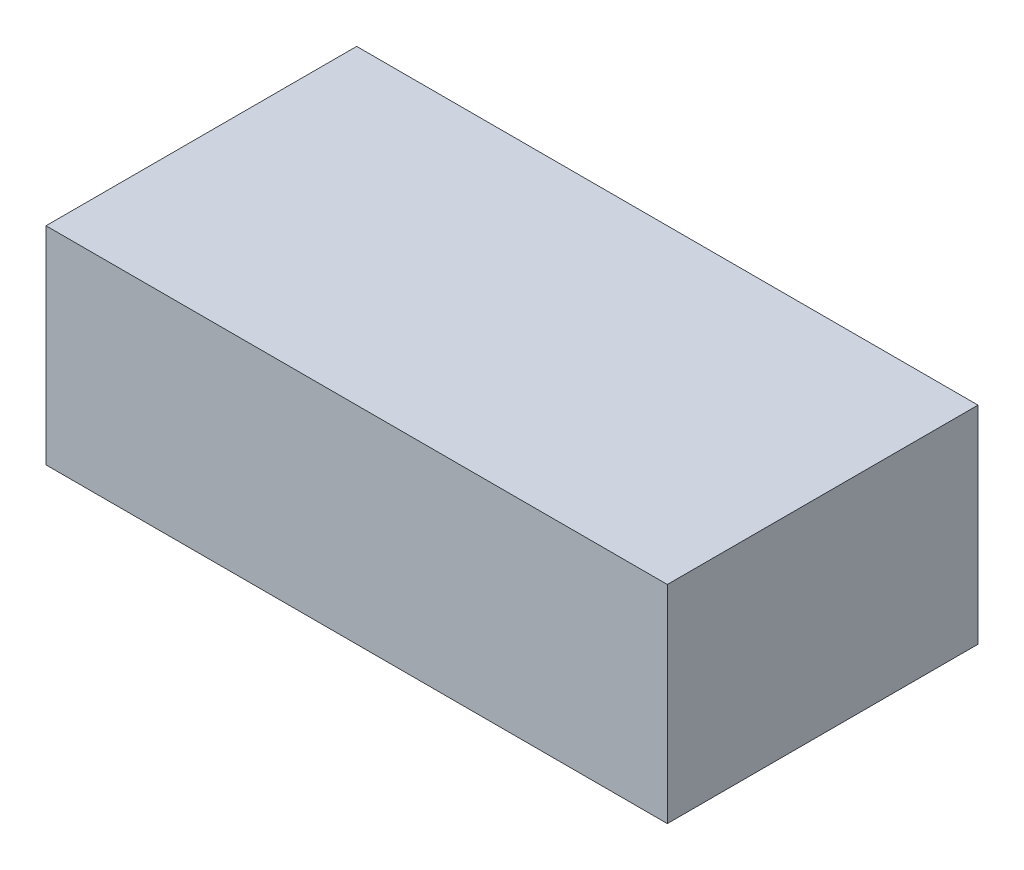
SolidWorks part; units mm, degrees
material "ESC"
ref_plane "Front Plane" through (0, 0, 0) normal (0, 0, 1) x (1, 0, 0)
ref_plane "Top Plane" through (0, 0, 0) normal (0, 1, 0) x (1, 0, 0)
ref_plane "Right Plane" through (0, 0, 0) normal (1, 0, 0) x (0, 0, -1)
sketch "Sketch2" plane through (0, 0, 0) normal (0, 1, 0) x (1, 0, 0)
  line L1 (-15.7922, -6.2948) -> (22.3078, -6.2948)
  line L2 (-15.7922, -6.2948) -> (-15.7922, 12.7552)
  line L3 (-15.7922, 12.7552) -> (22.3078, 12.7552)
  line L4 (22.3078, -6.2948) -> (22.3078, 12.7552)
  dimension "D1" = 38.1
  dimension "D2" = 19.05
extrude "Boss-Extrude1" add sketch "Sketch2" along normal blind 12.7 contours L3 L4 L1 L2
sketch "Sketch3" plane through (0, 12.7, 0) normal (0, 1, 0) x (1, 0, 0)
  text T0 "ESC"
